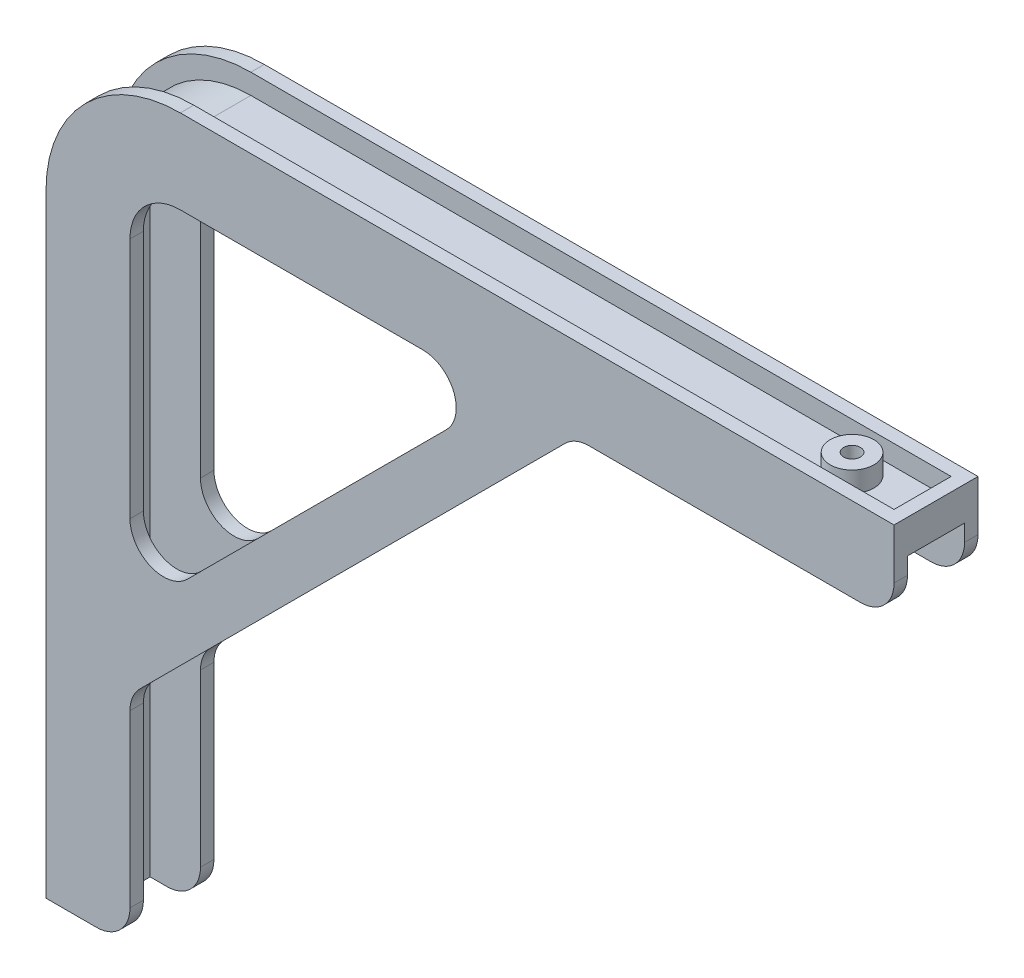
SolidWorks part; units mm, degrees
material "PMMA"
ref_plane "Plan de face" through (0, 0, 0) normal (0, 0, 1) x (1, 0, 0)
ref_plane "Plan de dessus" through (0, 0, 0) normal (0, 1, 0) x (1, 0, 0)
ref_plane "Plan de droite" through (0, 0, 0) normal (1, 0, 0) x (0, 0, -1)
sketch "Esquisse1" plane through (0, 0, 0) normal (0, 0, 1) x (1, 0, 0)
  line L0 (0, 0) -> (-212.5, 0)
  line L1 (-242.5, -30) -> (-242.5, -212.5)
  line L2 (-242.5, -212.5) -> (-252.5, -212.5)
  line L3 (-252.5, -212.5) -> (-252.5, -30)
  line L4 (-212.5, 10) -> (0, 10)
  line L5 (0, 10) -> (0, 0)
  arc A0 (-242.5, -30) -> (-212.5, 0) centre (-212.5, -30) cw
  arc A1 (-252.5, -30) -> (-212.5, 10) centre (-212.5, -30) cw
  point P11 (-252.5, 10)
  dimension "D4" = 30
  dimension "D5" = 40
  dimension "D1" = 10
  dimension "D2" = 252.5
  dimension "D3" = 222.5
extrude "Extrusion1" add sketch "Esquisse1" along normal mid plane 25
sketch "Esquisse2" plane through (-242.5, 0, 0) normal (1, 0, 0) x (0, 0, -1)
  line L0 (-12.5, 10) -> (12.5, 10) construction
  circle A0 centre (0, -50) radius 3
  circle A1 centre (0, -175) radius 3
  dimension "D1" = 6
  dimension "D2" = 60
  dimension "D3" = 125
extrude "Enlèv. mat.-Extru.1" cut sketch "Esquisse2" against normal through all
sketch "Esquisse3" plane through (0, 0, 0) normal (0, -1, 0) x (1, 0, 0)
  line L0 (0, 12.5) -> (0, -12.5) construction
  circle A0 centre (-25, 0) radius 2.5
  dimension "D1" = 5
  dimension "D2" = 25
extrude "Enlèv. mat.-Extru.2" cut sketch "Esquisse3" against normal through all
shell "Coque1" thickness 4
sketch "Esquisse4" plane through (0, 0, 12.5) normal (0, 0, 1) x (1, 0, 0)
  line L0 (-212.5, 0) -> (0, 0) construction
  line L1 (-242.5, -212.5) -> (-242.5, -30) construction
  line L2 (-212.5, 0) -> (0, 0)
  line L3 (-242.5, -212.5) -> (-242.5, -30)
  line L4 (-227.5, -202.5) -> (-227.5, -151.6421)
  line L5 (-212.5, -15) -> (-140.3553, -15)
  line L6 (-242.5, -212.5) -> (-237.5, -212.5)
  line L7 (0, 0) -> (0, -5)
  line L8 (-210.4289, -109.2157) -> (-133.2843, -32.0711)
  line L9 (-224.5711, -144.5711) -> (-97.9289, -17.9289)
  line L10 (-90.8579, -15) -> (-10, -15)
  line L11 (-212.5, -15) -> (0, -15) construction
  line L12 (-227.5, -102.1447) -> (-227.5, -30)
  line L13 (-227.5, -212.5) -> (-227.5, -30) construction
  arc A0 (-212.5, 0) -> (-242.5, -30) centre (-212.5, -30) ccw construction
  arc A1 (-212.5, 0) -> (-242.5, -30) centre (-212.5, -30) ccw
  arc A2 (-212.5, -15) -> (-227.5, -30) centre (-212.5, -30) ccw
  arc A3 (-10, -15) -> (0, -5) centre (-10, -5) ccw
  arc A4 (-237.5, -212.5) -> (-227.5, -202.5) centre (-237.5, -202.5) ccw
  arc A5 (-227.5, -102.1447) -> (-210.4289, -109.2157) centre (-217.5, -102.1447) ccw
  arc A6 (-133.2843, -32.0711) -> (-140.3553, -15) centre (-140.3553, -25) ccw
  arc A7 (-97.9289, -17.9289) -> (-90.8579, -15) centre (-90.8579, -25) cw
  arc A8 (-227.5, -151.6421) -> (-224.5711, -144.5711) centre (-217.5, -151.6421) cw
  point P22 (-227.5, -126.2868)
  point P27 (-95, -15)
  point P30 (-227.5, -147.5)
  dimension "D5" = 10
  dimension "D2" = 15
  dimension "D3" = 45
  dimension "D4" = 65
  dimension "D1" = 15
extrude "Extrusion2" add sketch "Esquisse4" against normal blind 4
mirror "Symétrie1" about plane through (0, 0, 0) normal (0, 0, 1) of "Extrusion2"
